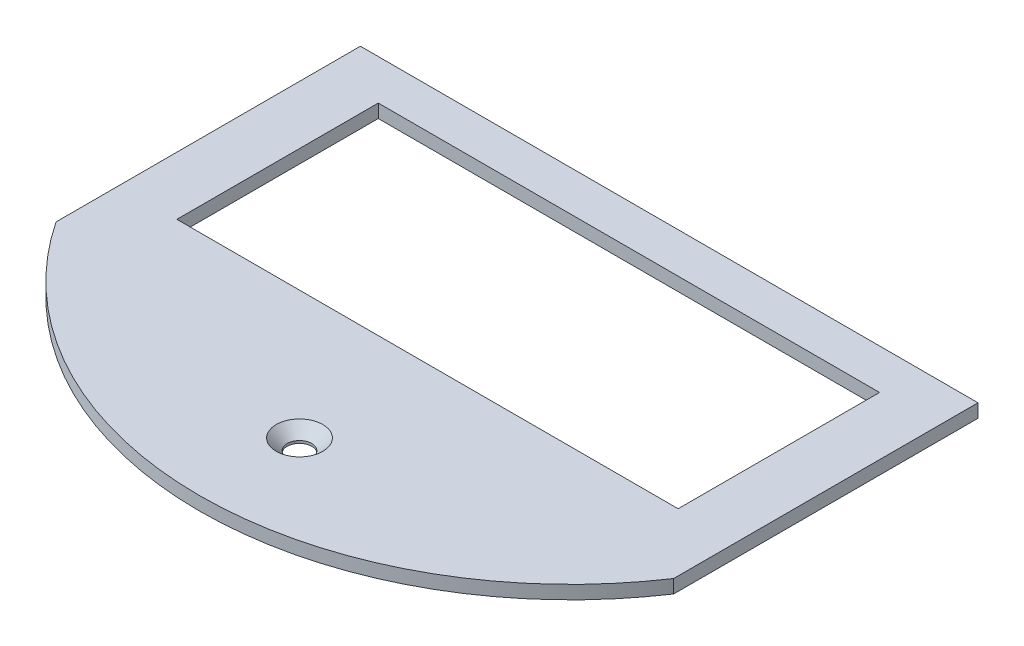
SolidWorks part; units mm, degrees
material "3.3320 (EN-AW 5019)"
ref_plane "Спереди" through (0, 0, 0) normal (0, 0, 1) x (1, 0, 0)
ref_plane "Сверху" through (0, 0, 0) normal (0, 1, 0) x (1, 0, 0)
ref_plane "Справа" through (0, 0, 0) normal (1, 0, 0) x (0, 0, -1)
sketch "Эскиз1" plane through (0, 0, 0) normal (0, 1, 0) x (1, 0, 0)
  line L0 (0, 0) -> (138, 0)
  line L1 (138, 0) -> (138, -68)
  line L2 (0, 0) -> (0, -68)
  arc A0 (0, -68) -> (138, -68) centre (69, -22) ccw
  dimension "D3" = 22
  dimension "D1" = 138
  dimension "D2" = 68
extrude "Бобышка-Вытянуть1" add sketch "Эскиз1" along normal blind 3
sketch "Эскиз2" plane through (0, 3, 0) normal (0, 1, 0) x (1, 0, 0)
  line L0 (138, 0) -> (0, 0) construction
  line L1 (13, -9) -> (125, -9)
  line L2 (13, -9) -> (13, -54)
  line L3 (13, -54) -> (125, -54)
  line L4 (125, -9) -> (125, -54)
  line L5 (0, 0) -> (0, -68) construction
  dimension "D1" = 112
  dimension "D2" = 45
  dimension "D3" = 9
  dimension "D4" = 13
extrude "Вырез-Вытянуть1" cut sketch "Эскиз2" against normal through all
hole_wizard "Зенковка для  винта с плоской головкой M51" positions "Эскиз4" profile "Эскиз3" countersink size "M5" standard "Ansi Metric" end condition through all
sketch "Эскиз4" plane through (0, 3, 0) normal (0, 1, 0) x (1, 0, 0)
  line L0 (0, 0) -> (0, -68) construction
  line L1 (138, 0) -> (0, 0) construction
  point P0 (69, -82.6)
  dimension "D1" = 69
  dimension "D2" = 82.6
sketch "Эскиз3" plane through (69, 3, 82.6) normal (1, 0, 0) x (0, 0, 1)
  line L0 (0, 0) -> (0, 3)
  line L1 (0, 3) -> (2.75, 3)
  line L2 (2.75, 3) -> (2.75, 2.45)
  line L3 (2.75, 2.45) -> (5.2, 0)
  line L5 (5.2, 0) -> (0, 0)
  line L6 (-2.75, 2.45) -> (-5.2, 0) construction
  line L11 (0, -6.35) -> (0, 107.95) construction
  dimension "Диаметр сквозного отверстия" = 5.5
  dimension "Глубина сквозного отверстия" = 3
  dimension "Диаметр передней зенковки" = 10.4
  dimension "Угол передней зенковки" = 90
